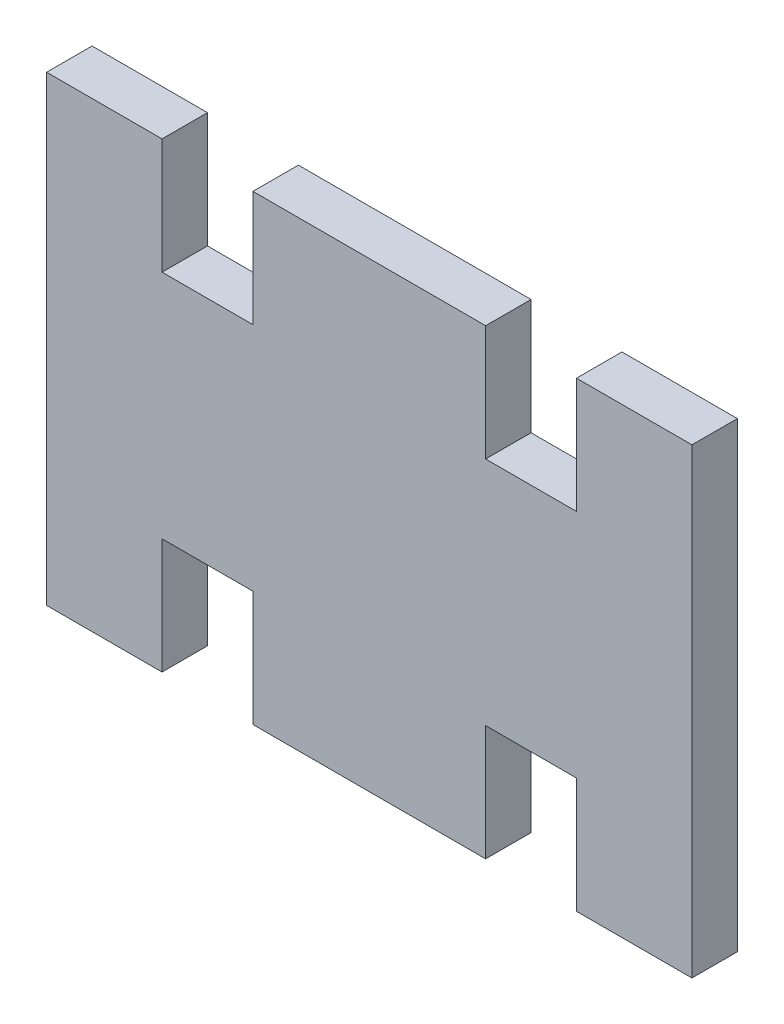
SolidWorks part; units mm, degrees
ref_plane "Alzado" through (0, 0, 0) normal (0, 0, 1) x (1, 0, 0)
ref_plane "Planta" through (0, 0, 0) normal (0, 1, 0) x (1, 0, 0)
ref_plane "Vista lateral" through (0, 0, 0) normal (1, 0, 0) x (0, 0, -1)
sketch "Croquis1" plane through (0, 0, 0) normal (0, 0, 1) x (1, 0, 0)
  line L0 (-35.5, 25.4) -> (-22.8, 25.4)
  line L1 (35.5, -25.4) -> (-35.5, -25.4) construction
  line L2 (35.5, -25.4) -> (35.5, 25.4)
  line L3 (35.5, 25.4) -> (-35.5, 25.4) construction
  line L4 (-35.5, -25.4) -> (-35.5, 25.4)
  line L5 (35.5, -25.4) -> (-35.5, 25.4) construction
  line L6 (35.5, 25.4) -> (-35.5, -25.4) construction
  line L7 (-22.8, 25.4) -> (-22.8, 12.7)
  line L8 (-22.8, 12.7) -> (-12.8, 12.7)
  line L9 (-12.8, 12.7) -> (-12.8, 25.4)
  line L10 (0, 25.4) -> (0, -25.4) construction
  line L11 (-35.5, 0) -> (35.5, 0) construction
  line L12 (12.8, 12.7) -> (12.8, 25.4)
  line L13 (22.8, 12.7) -> (12.8, 12.7)
  line L14 (22.8, 25.4) -> (22.8, 12.7)
  line L15 (35.5, 25.4) -> (22.8, 25.4)
  line L16 (35.5, -25.4) -> (-35.5, 25.4) construction
  line L17 (35.5, 25.4) -> (-35.5, -25.4) construction
  line L18 (35.5, -25.4) -> (-35.5, -25.4) construction
  line L19 (35.5, -25.4) -> (22.8, -25.4)
  line L20 (22.8, -25.4) -> (22.8, -12.7)
  line L21 (22.8, -12.7) -> (12.8, -12.7)
  line L22 (12.8, -12.7) -> (12.8, -25.4)
  line L23 (-12.8, -12.7) -> (-12.8, -25.4)
  line L24 (-22.8, -12.7) -> (-12.8, -12.7)
  line L25 (-22.8, -25.4) -> (-22.8, -12.7)
  line L26 (-35.5, -25.4) -> (-22.8, -25.4)
  line L27 (-12.8, 25.4) -> (12.8, 25.4)
  line L28 (-12.8, -25.4) -> (12.8, -25.4)
  point P0 (0, 0)
  dimension "D1" = 50.8
  dimension "D2" = 71
  dimension "D3" = 12.7
  dimension "D4" = 12.7
  dimension "D5" = 12.7
extrude "Saliente-Extruir1" add sketch "Croquis1" along normal blind 5
